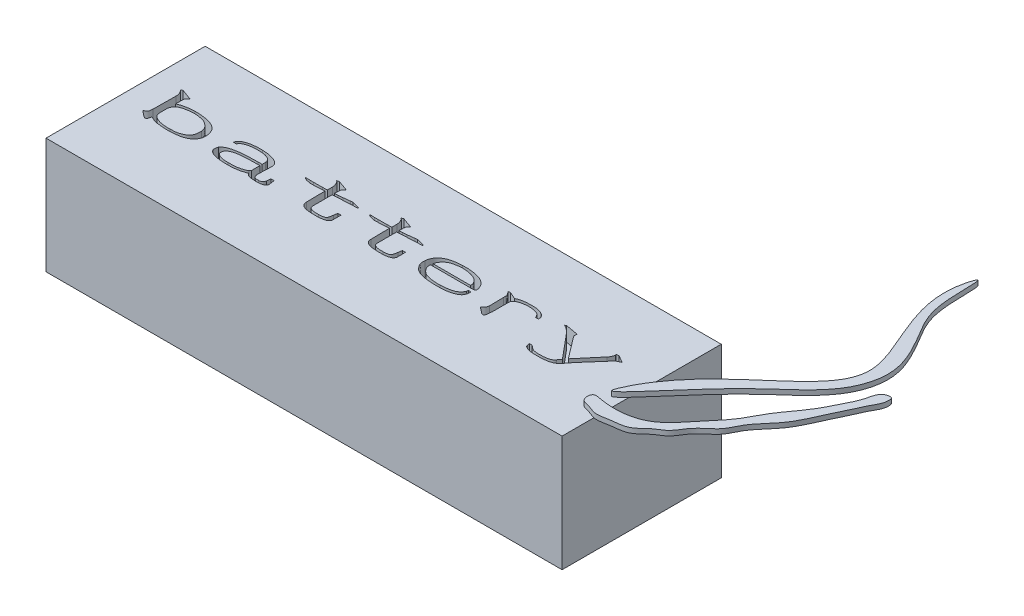
SolidWorks part; units mm, degrees
ref_plane "前视基准面" through (0, 0, 0) normal (0, 0, 1) x (1, 0, 0)
ref_plane "上视基准面" through (0, 0, 0) normal (0, 1, 0) x (1, 0, 0)
ref_plane "右视基准面" through (0, 0, 0) normal (1, 0, 0) x (0, 0, -1)
sketch "草图1" plane through (0, 0, 0) normal (0, 1, 0) x (1, 0, 0)
  line L1 (-53.5, -16.5) -> (53.5, -16.5)
  line L2 (-53.5, -16.5) -> (-53.5, 16.5)
  line L3 (-53.5, 16.5) -> (53.5, 16.5)
  line L4 (53.5, -16.5) -> (53.5, 16.5)
  line L5 (-53.5, -16.5) -> (53.5, 16.5) construction
  line L6 (-53.5, 16.5) -> (53.5, -16.5) construction
  point P0 (0, 0)
extrude "凸台-拉伸1" add sketch "草图1" along normal blind 24
sketch "草图3" plane through (0, 24, 0) normal (0, 1, 0) x (1, 0, 0)
  line L0 (53.5, -16.5) -> (53.5, 16.5) construction
  spline S0 degree 3 poles (49.9797, -6.817) (58.38, 11.7632) (85.832, 21.144) (65.6716, 42.3971) (69.9773, 55.3351) (69.5985, 44.1734) (72.4311, 38.9498) (78.4878, 29.3935) (75.5308, 19.3687) (66.1034, 11.386) (61.05, 6.1794) (49.9797, -6.817) (58.38, 11.7632) (85.832, 21.144) knots -0.202749 -0.086389 -0.025649 0 0.257086 0.455035 0.465272 0.505329 0.579343 0.660887 0.722727 0.797251 0.913611 0.974351 1 1.257086 1.455035 1.465272 only from (52.7958, -0.8368) to (52.7958, -0.8368)
  spline S1 degree 3 poles (49.9639, -6.4828) (54.9641, -7.5538) (61.145, -6.9549) (65.9743, -0.5667) (69.556, 3.3422) (72.1619, 8.8788) (75.5934, 12.7315) (77.7125, 17.3849) (79.264, 20.209) (79.5705, 23.0954) (81.0208, 23.5737) (81.8713, 23.7068) (82.1519, 21.7311) (80.8753, 20.1347) (79.8203, 17.3762) (77.7891, 13.5521) (75.7573, 7.9502) (71.5017, 4.1842) (69.8054, -0.1739) (66.4265, -2.0564) (64.9608, -5.494) (62.643, -6.6244) (61.3634, -7.9211) (59.4688, -9.5006) (57.0969, -9.4638) (54.9729, -9.9457) (53.2755, -10.0705) (51.9445, -9.2122) (50.711, -9.1054) (49.8176, -8.4114) (49.9639, -6.4828) (54.9641, -7.5538) (61.145, -6.9549) knots -0.036283 -0.028845 -0.010803 0 0.105259 0.16575 0.232822 0.265985 0.349341 0.387282 0.41831 0.451065 0.458175 0.464843 0.472484 0.50671 0.526789 0.561102 0.638059 0.703277 0.727658 0.776022 0.812732 0.834144 0.851343 0.868011 0.906932 0.918078 0.934532 0.956495 0.963717 0.971155 0.989197 1 1.105259 1.16575 1.232822 only from (51.4399, -6.788) to (51.4399, -6.788)
extrude "凸台-拉伸2" add sketch "草图3" along normal blind 1
sketch "草图4" plane through (0, 24, 0) normal (0, 1, 0) x (1, 0, 0)
  text T0 "battery" font "汉仪长仿宋体" height in points 36
extrude "切除-拉伸1" cut sketch "草图4" against normal blind 3
